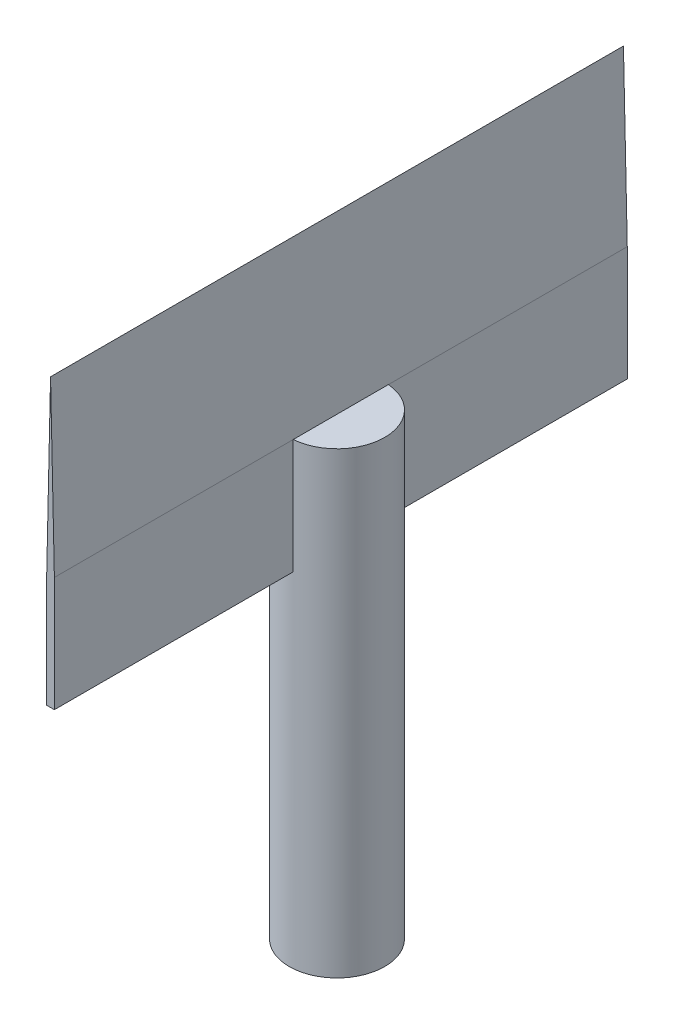
SolidWorks part; units mm, degrees
ref_plane "Front Plane" through (0, 0, 0) normal (0, 0, 1) x (1, 0, 0)
ref_plane "Top Plane" through (0, 0, 0) normal (0, 1, 0) x (1, 0, 0)
ref_plane "Right Plane" through (0, 0, 0) normal (1, 0, 0) x (0, 0, -1)
sketch "Sketch2" plane through (0, 0, 0) normal (0, 1, 0) x (1, 0, 0)
  circle A0 centre (0, 0) radius 10
  circle A1 centre (0, 0) radius 12.5
  dimension "D1" = 2.5
  dimension "D2" = 20
extrude "Boss-Extrude3" add sketch "Sketch2" along normal blind 90
sketch "Sketch3" plane through (0, 90, 0) normal (0, 1, 0) x (1, 0, 0)
  circle A0 centre (0, 0) radius 12.5
  circle A1 centre (0, 0) radius 12.5 construction
extrude "Boss-Extrude4" add sketch "Sketch3" along normal blind 30
sketch "Sketch5" plane through (0, 0, 0) normal (0, 0, 1) x (1, 0, 0)
  line L0 (-1, 90) -> (1, 90)
  line L1 (0, -13.75) -> (0, 13.75) construction
  line L2 (-1, 90) -> (-1, 120)
  line L3 (1, 90) -> (1, 120)
  line L4 (12.5, 120) -> (-12.5, 120) construction
  line L5 (-1, 120) -> (0, 165)
  line L6 (0, 165) -> (1, 120)
  point P2 (0, 90)
  point P5 (0, 167.6823)
  dimension "D1" = 2
  dimension "D2" = 30
  dimension "D3" = 45
extrude "Boss-Extrude5" add sketch "Sketch5" along normal mid plane 150
